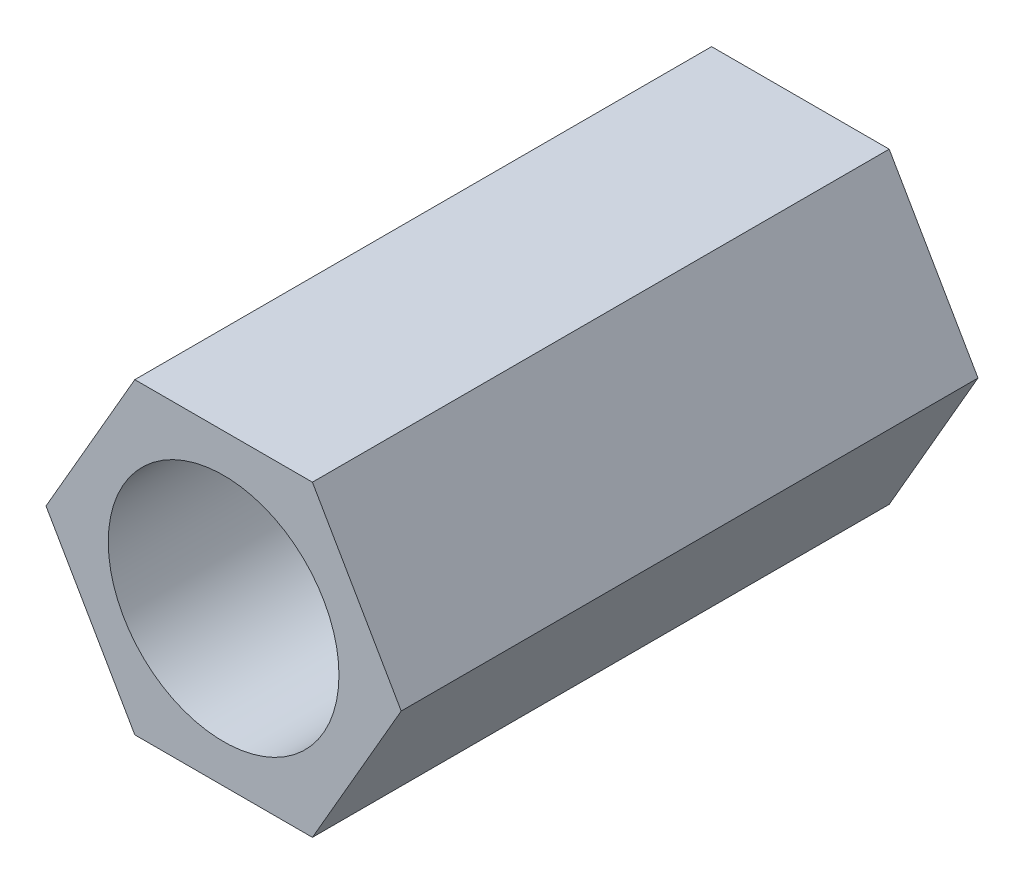
SolidWorks part; units mm, degrees
ref_plane "前视基准面" through (0, 0, 0) normal (0, 0, 1) x (1, 0, 0)
ref_plane "上视基准面" through (0, 0, 0) normal (0, 1, 0) x (1, 0, 0)
ref_plane "右视基准面" through (0, 0, 0) normal (1, 0, 0) x (0, 0, -1)
other "Configuration Table"
sketch "草图1" plane through (0, 0, 0) normal (0, 0, 1) x (1, 0, 0)
  line L1 (2.3094, 0) -> (1.1547, 2)
  line L2 (1.1547, 2) -> (-1.1547, 2)
  line L3 (-1.1547, 2) -> (-2.3094, 0)
  line L4 (-2.3094, 0) -> (-1.1547, -2)
  line L5 (-1.1547, -2) -> (1.1547, -2)
  line L6 (1.1547, -2) -> (2.3094, 0)
  circle A0 centre (0, 0) radius 2 construction
  circle A1 centre (0, 0) radius 1.5
  dimension "D1" = 2
extrude "凸台-拉伸1" add sketch "草图1" along normal blind 7.5
